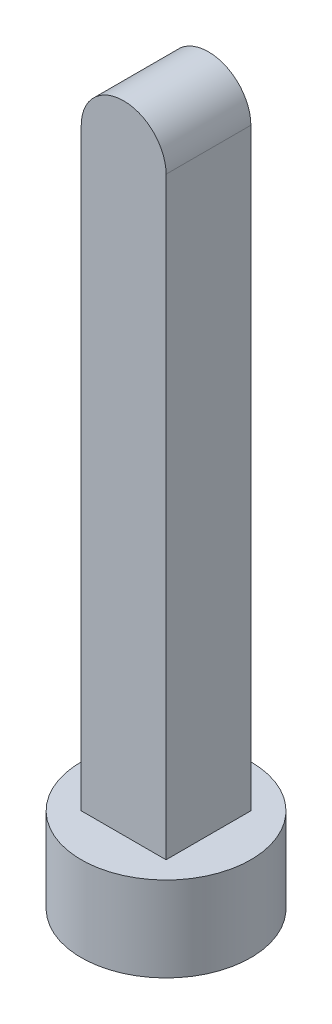
SolidWorks part; units mm, degrees
ref_plane "Plan de face" through (0, 0, 0) normal (0, 0, 1) x (1, 0, 0)
ref_plane "Plan de dessus" through (0, 0, 0) normal (0, 1, 0) x (1, 0, 0)
ref_plane "Plan de droite" through (0, 0, 0) normal (1, 0, 0) x (0, 0, -1)
sketch "Esquisse1" plane through (0, 0, 0) normal (0, 1, 0) x (1, 0, 0)
  line L1 (-12.5, 12.5) -> (12.5, 12.5)
  line L2 (-12.5, 12.5) -> (-12.5, -12.5)
  line L3 (-12.5, -12.5) -> (12.5, -12.5)
  line L4 (12.5, 12.5) -> (12.5, -12.5)
  point P7 (2.933, -15.0701)
  dimension "D1" = 25
  dimension "D2" = 25
  dimension "D3" = 12.5
  dimension "D4" = 12.5
extrude "Boss.-Extru.1" add sketch "Esquisse1" along normal blind 200
sketch "Esquisse2" plane through (0, 0, 12.5) normal (0, 0, 1) x (1, 0, 0)
  line L0 (-12.5, 200) -> (12.5, 200) construction
  line L1 (-12.5, 200) -> (12.5, 200)
  arc A0 (-12.5, 200) -> (12.5, 200) centre (0, 200) cw
extrude "Boss.-Extru.2" add sketch "Esquisse2" against normal blind 25
sketch "Esquisse3" plane through (0, 0, 0) normal (0, -1, 0) x (1, 0, 0)
  circle A0 centre (0, 0) radius 25
  dimension "D1" = 50
extrude "Boss.-Extru.3" add sketch "Esquisse3" against normal blind 25
